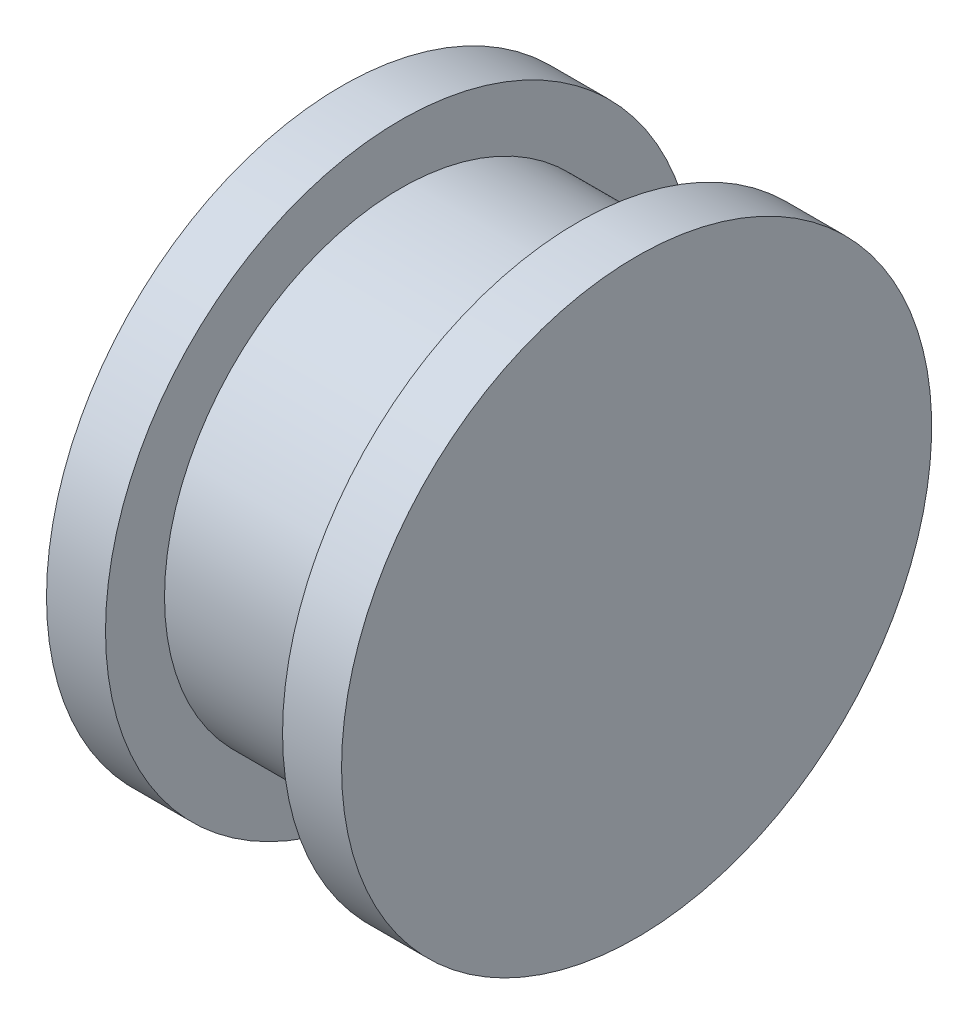
SolidWorks part; units mm, degrees
ref_plane "Plan de face" through (0, 0, 0) normal (0, 0, 1) x (1, 0, 0)
ref_plane "Plan de dessus" through (0, 0, 0) normal (0, 1, 0) x (1, 0, 0)
ref_plane "Plan de droite" through (0, 0, 0) normal (1, 0, 0) x (0, 0, -1)
sketch "Esquisse1" plane through (0, 0, 0) normal (0, 0, 1) x (1, 0, 0)
  line L0 (0, 0) -> (19.9138, 0) construction
  line L1 (-4, -5) -> (-4, -4)
  line L2 (-4, -4) -> (-1, -4)
  line L3 (-1, -4) -> (-1, -5)
  line L4 (-1, -5) -> (0, -5)
  line L5 (0, -5) -> (0, 0)
  line L6 (0, 0) -> (-1, 0)
  line L7 (-1, 0) -> (-1, -3)
  line L8 (-1, -3) -> (-5, -3)
  line L9 (-5, -3) -> (-5, -5)
  line L10 (-5, -5) -> (-4, -5)
  dimension "D1" = 8
  dimension "D2" = 3
  dimension "D3" = 1
  dimension "D4" = 1
  dimension "D6" = 1
  dimension "D7" = 6
  dimension "D8" = 10
revolve "Révolution1" add sketch "Esquisse1" angle 360 about L0
